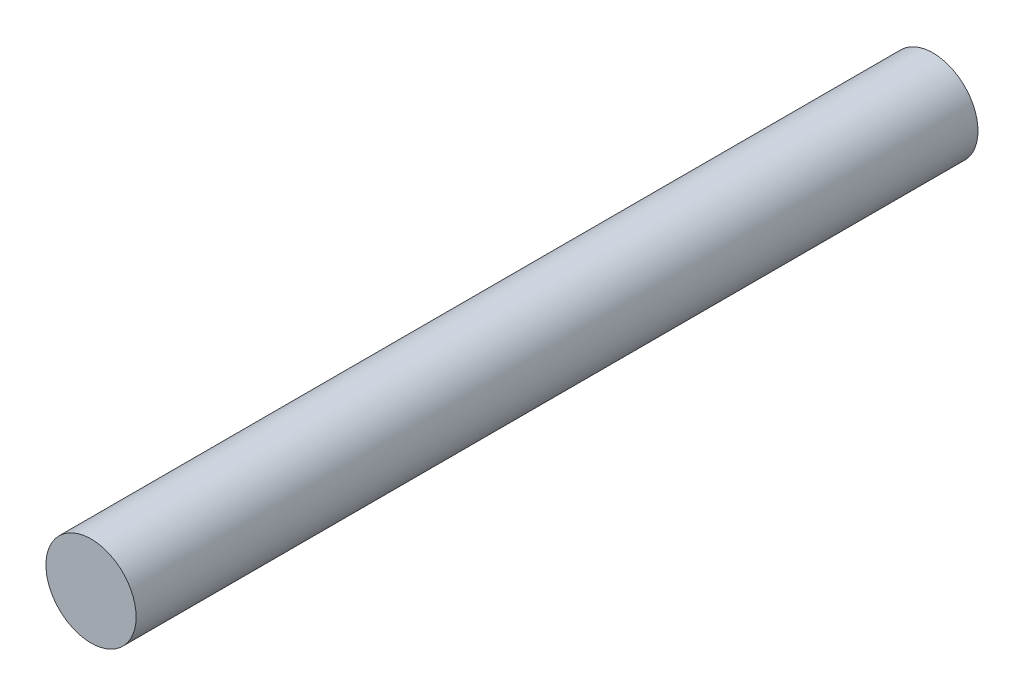
SolidWorks part; units mm, degrees
ref_plane "前视基准面" through (0, 0, 0) normal (0, 0, 1) x (1, 0, 0)
ref_plane "上视基准面" through (0, 0, 0) normal (0, 1, 0) x (1, 0, 0)
ref_plane "右视基准面" through (0, 0, 0) normal (1, 0, 0) x (0, 0, -1)
sketch "草图1" plane through (0, 0, 0) normal (0, 0, 1) x (1, 0, 0)
  circle A0 centre (0, 0) radius 3
  dimension "D1" = 6
extrude "凸台-拉伸1" add sketch "草图1" along normal blind 56
